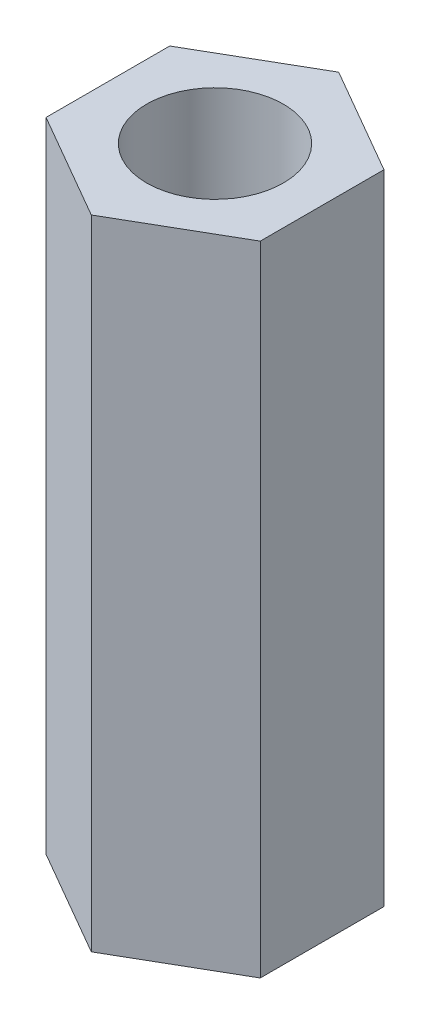
SolidWorks part; units mm, degrees
material "黄铜"
ref_plane "前视基准面" through (0, 0, 0) normal (0, 0, 1) x (1, 0, 0)
ref_plane "上视基准面" through (0, 0, 0) normal (0, 1, 0) x (1, 0, 0)
ref_plane "右视基准面" through (0, 0, 0) normal (1, 0, 0) x (0, 0, -1)
sketch "草图1" plane through (0, 0, 0) normal (0, 1, 0) x (1, 0, 0)
  line L0 (0, 2.7135) -> (0, 0) construction
  line L1 (0, -2.7135) -> (2.35, -1.3568)
  line L2 (2.35, -1.3568) -> (2.35, 1.3568)
  line L3 (2.35, 1.3568) -> (0, 2.7135)
  line L4 (0, 2.7135) -> (-2.35, 1.3568)
  line L5 (-2.35, 1.3568) -> (-2.35, -1.3568)
  line L6 (-2.35, -1.3568) -> (0, -2.7135)
  circle A1 centre (0, 0) radius 2.35 construction
  circle A2 centre (0, 0) radius 1.5
  dimension "D1" = 3
  dimension "D2" = 4.7
extrude "凸台-拉伸1" add sketch "草图1" along normal blind 14
